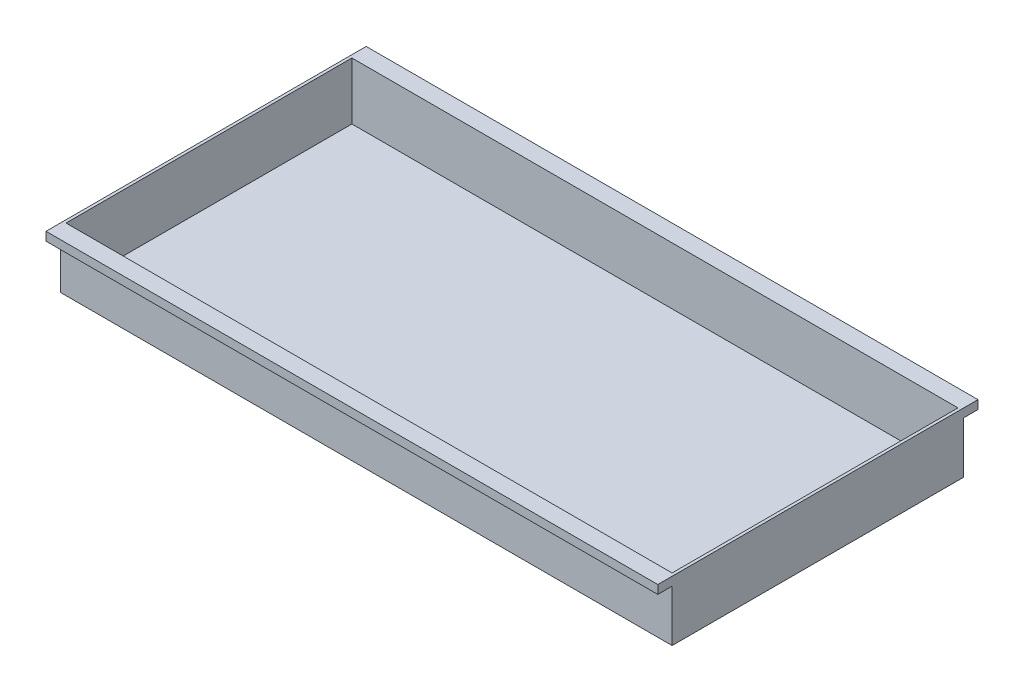
SolidWorks part; units mm, degrees
ref_plane "Alzado" through (0, 0, 0) normal (0, 0, 1) x (1, 0, 0)
ref_plane "Planta" through (0, 0, 0) normal (0, 1, 0) x (1, 0, 0)
ref_plane "Vista lateral" through (0, 0, 0) normal (1, 0, 0) x (0, 0, -1)
sketch "Croquis1" plane through (0, 0, 0) normal (0, 1, 0) x (1, 0, 0)
  line L1 (535, -255) -> (-535, -255)
  line L2 (535, -255) -> (535, 255)
  line L3 (535, 255) -> (-535, 255)
  line L4 (-535, -255) -> (-535, 255)
  line L5 (535, -255) -> (-535, 255) construction
  line L6 (535, 255) -> (-535, -255) construction
  point P0 (0, 0)
  dimension "D1" = 1070
  dimension "D2" = 510
extrude "Extruir-Lámina1" add sketch "Croquis1" against normal blind 100 thin
sketch "Croquis2" plane through (0, -100, 0) normal (0, -1, 0) x (1, 0, 0)
  line L4 (-535, 255) -> (-535, -255)
  line L5 (-535, -255) -> (535, -255)
  line L6 (535, -255) -> (535, 255)
  line L7 (535, 255) -> (-535, 255)
  line L8 (-535, 255) -> (-535, -255)
  line L9 (-535, -255) -> (535, -255)
  line L10 (535, -255) -> (535, 255)
  line L11 (535, 255) -> (-535, 255)
  dimension "D1" = 0
extrude "Extruir1" add sketch "Croquis2" along normal blind 5
sketch "Croquis3" plane through (0, 0, 0) normal (0, 1, 0) x (1, 0, 0)
  line L0 (535, -255) -> (535, 255) construction
  line L1 (-535, 255) -> (535, 255)
  line L2 (-535, 255) -> (-535, 280)
  line L3 (-535, 280) -> (535, 280)
  line L4 (535, 255) -> (535, 280)
  line L5 (0, 0) -> (732.5661, 0) construction
  line L6 (535, -255) -> (535, -280)
  line L7 (-535, -280) -> (535, -280)
  line L8 (-535, -255) -> (-535, -280)
  line L9 (-535, -255) -> (535, -255)
  dimension "D1" = 25
extrude "Extruir2" add sketch "Croquis3" against normal blind 15
